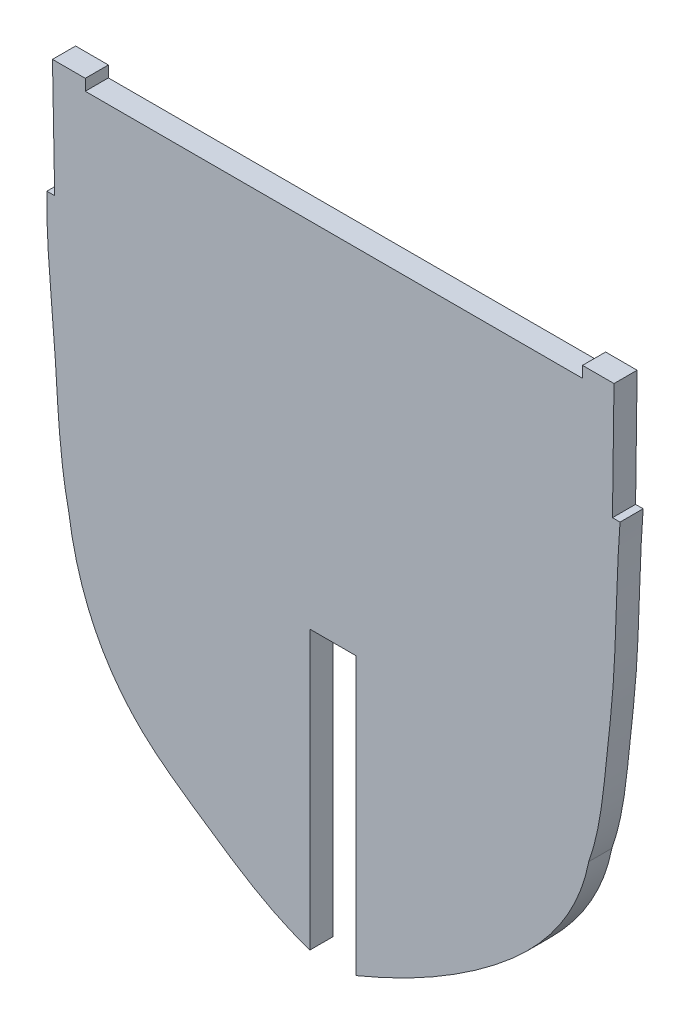
SolidWorks part; units mm, degrees
ref_plane "前视基准面" through (0, 0, 0) normal (0, 0, 1) x (1, 0, 0)
ref_plane "上视基准面" through (0, 0, 0) normal (0, 1, 0) x (1, 0, 0)
ref_plane "右视基准面" through (0, 0, 0) normal (1, 0, 0) x (0, 0, -1)
other "Configuration Table"
sketch "草图1" plane through (0, 0, 0) normal (0, 0, 1) x (1, 0, 0)
  line L0 (376.6667, 613.5) -> (1883.3333, 613.5) construction
  line L13 (192.0157, 236.2152) -> (197.6918, 236.2152)
  line L14 (197.6918, 236.2152) -> (197.6918, 234.2721)
  line L15 (197.6918, 234.2721) -> (283.7162, 234.2721)
  line L16 (283.7162, 234.2721) -> (283.7162, 236.2152)
  line L17 (283.7162, 236.2152) -> (289.1665, 236.2152)
  line L18 (289.1665, 236.2152) -> (288.9, 215.9798)
  line L19 (288.9, 215.9798) -> (290.2088, 215.9798)
  line L20 (192.0157, 236.2152) -> (192.3973, 215.9798)
  line L21 (192.3973, 215.9798) -> (191.0447, 215.9798)
  line L29 (236.5599, 169.1139) -> (236.5599, 125.0327)
  line L31 (244.5599, 169.1139) -> (244.5599, 125.2007)
  line L33 (236.5599, 169.1139) -> (236.5599, 173.1139)
  line L34 (236.5599, 173.1139) -> (244.5599, 173.1139)
  line L35 (244.5599, 173.1139) -> (244.5599, 169.1139)
  spline S3 degree 3 poles (191.0447, 215.9798) (190.9067, 208.304) (192.7894, 192.9808) (193.135, 177.5337) (194.8145, 169.9054) knots 0 0 0 0 0.496472 1 1 1 1
  spline S4 degree 3 poles (194.8145, 169.9054) (195.6101, 164.1769) (198.3466, 154.4923) (207.0217, 142.7874) (216.3904, 136.3997) (225.9519, 129.821) (232.2711, 126.4325) (236.5599, 125.0327) knots 0 0 0 0 0.262955 0.448389 0.647829 0.773904 0.974785 0.974785 0.974785 0.974785
  spline S5 degree 3 poles (244.5599, 125.2007) (246.5109, 126.0056) (253.8423, 129.2359) (270.2859, 138.5995) (282.5986, 151.1788) (284.7996, 162.3924) knots 0.030116 0.030116 0.030116 0.030116 0.138265 0.441022 1 1 1 1
  spline S6 degree 3 poles (284.7996, 162.3924) (286.7595, 167.8935) (287.5799, 177.0298) (289.6498, 194.8977) (289.5274, 207.1499) (290.2088, 215.9798) knots 0 0 0 0 0.321928 0.507408 1 1 1 1
  dimension "D1" = 43.9133
extrude "凸台-拉伸1" add sketch "草图1" along normal blind 4
